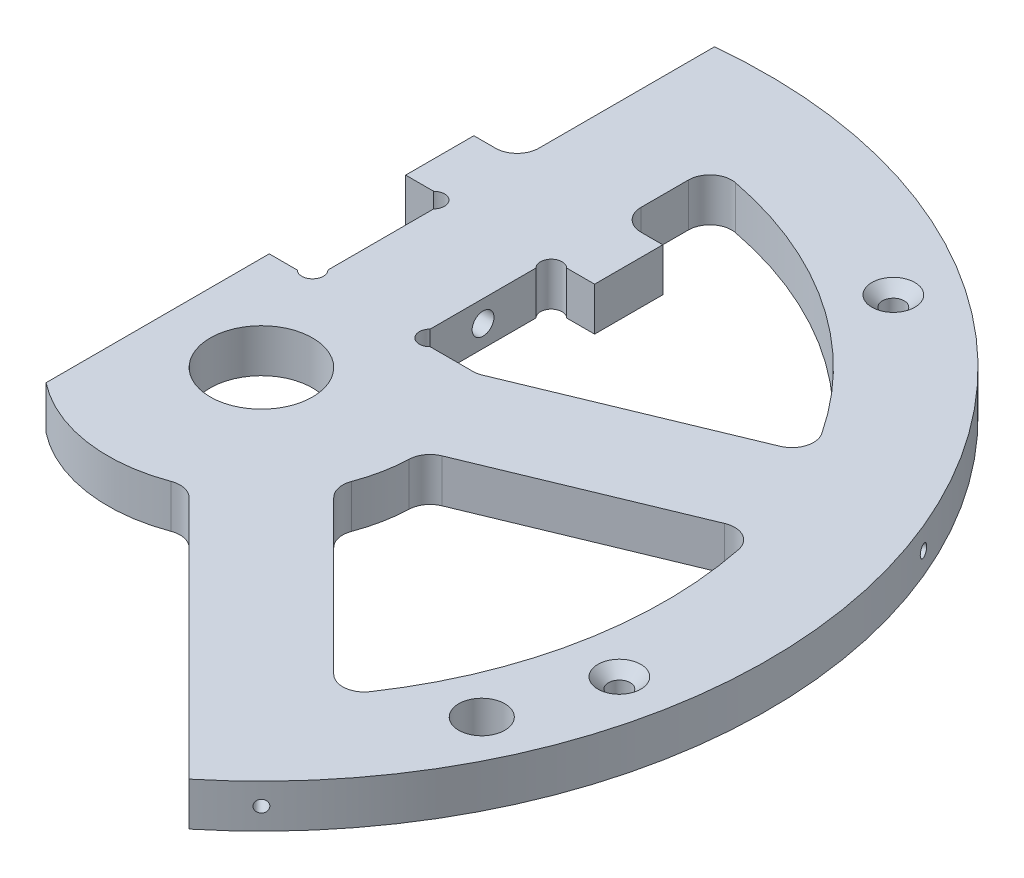
SolidWorks part; units mm, degrees
material "6061 Alloy"
ref_plane "Front Plane" through (0, 0, 0) normal (0, 0, 1) x (1, 0, 0)
ref_plane "Top Plane" through (0, 0, 0) normal (0, 1, 0) x (1, 0, 0)
ref_plane "Right Plane" through (0, 0, 0) normal (1, 0, 0) x (0, 0, -1)
sketch "Sketch1" plane through (0, 0, 0) normal (0, 1, 0) x (1, 0, 0)
  line L0 (0, 0) -> (0, 74.3) construction
  line L1 (0, 0) -> (52.538, -52.538) construction
  line L2 (20.3033, -9.6967) -> (46.898, -36.2914)
  line L3 (7.5, 15) -> (7.5, 35)
  line L4 (-7.5, -3.1066) -> (-5.3033, -5.3033) construction
  line L5 (-7.5, 21.2132) -> (-7.5, 14.1697) construction
  line L6 (-7.5, -3.1066) -> (-7.5, 74.3) construction
  line L7 (7.5, 3.1066) -> (7.5, 74.3) construction
  line L8 (-7.5, -3.1066) -> (47.2347, -57.8413) construction
  line L9 (7.5, 3.1066) -> (57.8413, -47.2347) construction
  line L10 (46.898, -36.2914) -> (57.573, -46.9664) construction
  line L11 (7.5, 58.8238) -> (7.5, 73.9205) construction
  line L12 (0, 0) -> (68.6442, 28.4334) construction
  line L13 (22.4686, 1.1888) -> (57.2162, 15.5818)
  line L14 (-2.8701, 6.9291) -> (0, 8.1179) construction
  line L15 (2.8701, -6.9291) -> (5.7403, -5.7403) construction
  line L16 (2.8701, -6.9291) -> (71.5144, 21.5043) construction
  line L17 (5.7403, -5.7403) -> (13.2403, -2.6336) construction
  line L18 (7.5, 3.1066) -> (13.2403, -2.6336) construction
  line L19 (7.5, 3.1066) -> (7.5, 11.2245) construction
  line L20 (0, 8.1179) -> (7.5, 11.2245) construction
  line L21 (7.5, 11.2245) -> (9.0849, 11.881) construction
  line L22 (-2.8701, 6.9291) -> (65.7741, 35.3625) construction
  line L23 (51.476, 29.44) -> (65.4235, 35.2172) construction
  line L24 (65.4235, 35.2172) -> (65.7741, 35.3625)
  line L25 (57.2162, 15.5818) -> (71.1638, 21.3591) construction
  line L26 (71.1638, 21.3591) -> (71.5144, 21.5043)
  line L27 (13.2403, -2.6336) -> (20.3033, -9.6967) construction
  line L28 (13.85, 5) -> (7.5, 5) construction
  line L29 (13.85, 17.7321) -> (13.85, 15) construction
  line L30 (13.85, 45) -> (7.5, 45)
  line L31 (-13.85, 17.7321) -> (-13.85, 15) construction
  line L32 (13.85, 5) -> (-13.85, 45) construction
  line L33 (13.85, 45) -> (-13.85, 5) construction
  line L34 (-13.85, 35) -> (-7.5, 35)
  line L35 (-13.85, 35) -> (-13.85, 15) construction
  line L36 (-16.7705, 15) -> (-7.5, 15)
  line L37 (-7.5, 35) -> (-7.5, 15)
  line L38 (7.5, 15) -> (16.6148, 15)
  line L39 (7.5, 15) -> (7.5, 35)
  line L40 (7.5, 35) -> (13.85, 35)
  line L41 (13.85, 15) -> (13.85, 35) construction
  line L42 (13.2403, -2.6336) -> (22.4686, 1.1888) construction
  line L43 (7.5, 5) -> (-7.5274, 5) construction
  line L44 (-7.5, 5) -> (-13.85, 5) construction
  line L45 (-7.5274, 5) -> (0, 5) construction
  line L46 (0, 5) -> (-7.5, 5) construction
  line L47 (13.85, 5) -> (13.85, 13.8548) construction
  line L48 (16.6148, 15) -> (16.7283, 15.047)
  line L49 (16.7283, 15.047) -> (51.476, 29.44)
  line L50 (13.85, 13.8548) -> (13.85, 17.7321) construction
  line L51 (9.0849, 11.881) -> (13.85, 13.8548) construction
  line L52 (7.5, 11.2245) -> (7.5, 21.2132) construction
  line L53 (7.5, 21.2132) -> (7.5, 14.1697) construction
  line L54 (-5.3033, -5.3033) -> (9.6967, -20.3033) construction
  line L55 (9.6967, -20.3033) -> (46.9664, -57.573)
  line L56 (-7.5, -3.1066) -> (-7.5, 0) construction
  line L57 (-7.5, 0) -> (-7.5, 5) construction
  line L58 (-13.85, 5) -> (-13.85, 17.7321) construction
  line L59 (-7.5, 5) -> (-7.5, 21.2132) construction
  line L60 (-7.5, 14.1697) -> (-7.5, 15) construction
  line L61 (-7.5, 15) -> (-7.5, 35) construction
  line L62 (-13.85, 15) -> (-13.85, 35) construction
  line L63 (-13.85, 35) -> (-13.85, 45)
  line L64 (13.85, 15) -> (13.85, 35) construction
  line L65 (13.85, 35) -> (13.85, 45)
  line L66 (0, 45) -> (-7.5, 45) construction
  line L67 (-7.5, 45) -> (-13.85, 45)
  line L68 (7.5, 45) -> (0, 45) construction
  line L69 (7.5, 14.1697) -> (7.5, 15) construction
  line L70 (7.5, 35.8303) -> (7.5, 45) construction
  line L71 (7.5, 45) -> (7.5, 58.8238)
  line L72 (7.5, 35) -> (7.5, 35.8303) construction
  line L73 (-7.5, 35) -> (-7.5, 35.8303) construction
  line L74 (-7.5, 45) -> (-7.5, 73.9205)
  line L75 (-7.5, 35.8303) -> (-7.5, 45) construction
  line L77 (13.85, 13.8548) -> (16.6148, 15) construction
  arc A0 (46.9664, -57.573) -> (-7.5, 73.9205) centre (0, 0) ccw
  arc A1 (46.898, -36.2914) -> (57.2162, 15.5818) centre (0, 0) ccw
  arc A2 (-7.5, 73.9205) -> (46.9664, -57.573) centre (0, 0) ccw construction
  circle A3 centre (0, 0) radius 74.3 construction
  arc A4 (41.9314, -41.9314) -> (46.898, -36.2914) centre (0, 0) ccw construction
  circle A5 centre (0, 0) radius 59.3 construction
  arc A6 (36.2914, -46.898) -> (41.9314, -41.9314) centre (0, 0) ccw construction
  arc A7 (-7.5, 58.8238) -> (36.2914, -46.898) centre (0, 0) ccw construction
  arc A8 (7.5, 58.8238) -> (0, 59.3) centre (0, 0) ccw construction
  arc A9 (0, 59.3) -> (-7.5, 58.8238) centre (0, 0) ccw construction
  arc A10 (57.2162, 15.5818) -> (54.7861, 22.6931) centre (0, 0) ccw construction
  arc A11 (51.476, 29.44) -> (7.5, 58.8238) centre (0, 0) ccw
  arc A12 (54.7861, 22.6931) -> (51.476, 29.44) centre (0, 0) ccw construction
  arc A13 (20.3033, -9.6967) -> (22.4686, 1.1888) centre (0, 0) ccw
  circle A14 centre (0, 0) radius 7.5
  arc A15 (9.6967, -20.3033) -> (15.9099, -15.9099) centre (0, 0) ccw construction
  arc A16 (15.9099, -15.9099) -> (20.3033, -9.6967) centre (0, 0) ccw construction
  arc A17 (22.4686, 1.1888) -> (20.7873, 8.6104) centre (0, 0) ccw construction
  arc A18 (16.7283, 15.047) -> (13.85, 17.7321) centre (0, 0) ccw construction
  arc A19 (20.7873, 8.6104) -> (16.7283, 15.047) centre (0, 0) ccw construction
  arc A20 (13.85, 17.7321) -> (1.7801, 22.4295) centre (0, 0) ccw construction
  arc A21 (-7.5, 21.2132) -> (-13.85, 17.7321) centre (0, 0) ccw construction
  arc A22 (1.7801, 22.4295) -> (-13.85, 17.7321) centre (0, 0) ccw construction
  arc A23 (7.5, 21.2132) -> (0, 22.5) centre (0, 0) ccw construction
  arc A24 (0, 22.5) -> (-7.5, 21.2132) centre (0, 0) ccw construction
  arc A25 (-1.7801, 22.4295) -> (-13.85, 17.7321) centre (0, 0) ccw construction
  arc A26 (-16.7705, 15) -> (9.6967, -20.3033) centre (0, 0) ccw
  arc A27 (-13.85, 17.7321) -> (-16.7705, 15) centre (0, 0) ccw construction
  arc A28 (-16.7705, 15) -> (-1.7801, 22.4295) centre (0, 0) ccw construction
  arc A29 (-13.85, 17.7321) -> (-16.7705, 15) centre (0, 0) ccw construction
  arc A30 (-13.85, 17.7321) -> (-16.7705, 15) centre (0, 0) ccw construction
  arc A31 (-16.7705, 15) -> (7.5, 21.2132) centre (0, 0) ccw construction
  point P77 (0, 25)
  dimension "D1" = 148.6
  dimension "D11" = 45
  dimension "D12" = 15
  dimension "D2" = 135
  dimension "D6" = 67.5
  dimension "D9" = 27.7
  dimension "D10" = 40
  dimension "D13" = 5
  dimension "D14" = 10
  dimension "D15" = 10
  dimension "D3" = 7.5
  dimension "D4" = 7.5
  dimension "D5" = 15
  dimension "D7" = 7.5
  dimension "D8" = 7.5
extrude "Boss-Extrude1" add sketch "Sketch1" along normal mid plane 6.35 contours L31 A26 L55 A0 L74 L67 L63 L34 L37 L36 L49 A18 L29 L38 L3 L40 L65 L30 L71 A11 L2 A13 L13 A1 A14
hole_wizard "M5x0.8 Tapped Hole2" positions "Sketch2" profile "Sketch3" tap size "M5x0.8" standard "ANSI Metric"
sketch "Sketch2" plane through (0, 3.175, 0) normal (0, 1, 0) x (1, 0, 0)
  line L1 (0, 0) -> (-13.4234, 7.75) construction
  line L3 (13.4234, 7.75) -> (0, 0) construction
  line L4 (0, 0) -> (0, -15.5) construction
  circle A0 centre (0, 0) radius 15.5 construction
  point P10 (-13.4234, 7.75)
  point P12 (13.4234, 7.75)
  point P16 (0, -15.5)
  dimension "D1" = 31
  dimension "D2" = 120
  dimension "D3" = 120
sketch "Sketch3" plane through (0, 3.175, 15.5) normal (1, 0, 0) x (0, 0, 1)
  line L0 (0, 0) -> (0, 6.35)
  line L1 (0, 6.35) -> (2.1, 6.35)
  line L2 (2.1, 6.35) -> (2.1, 0)
  line L5 (2.1, 0) -> (0, 0)
  line L11 (0, -6.35) -> (0, 107.95) construction
  dimension "Thru Tap Drill Dia." = 4.2
  dimension "Thru Tap Drill Depth" = 6.35
ref_plane "Plane1" through (0, 0, -74.3) normal (0, 0, -1) x (-1, 0, 0)
hole_wizard "M2.2x0.45 Tapped Hole1" positions "Sketch4" profile "Sketch5" tap size "M2.2x0.45" standard "ANSI Metric"
sketch "Sketch4" plane through (0, 0, -74.3) normal (0, 0, -1) x (-1, 0, 0)
  point P0 (0, 0)
sketch "Sketch5" plane through (0, 0, -74.3) normal (1, 0, 0) x (0, 1, 0)
  line L0 (0, 0) -> (0, 10.5258)
  line L1 (0, 10.5258) -> (0.875, 10)
  line L2 (0.875, 10) -> (0.875, 0)
  line L5 (0.875, 0) -> (0, 0)
  line L10 (0, 10.5258) -> (-0.875, 10) construction
  line L11 (0, -6.35) -> (0, 107.95) construction
  dimension "Tap Drill Dia." = 1.75
  dimension "Tap Drill Depth" = 10
  dimension "Drill Angle" = 118
pattern_circular "CirPattern1" count 3 over 135 about axis through (0, 3.175, 0) along (0, -1, 0) of "M2.2x0.45 Tapped Hole1"
hole_wizard "M3 Clearance Hole1" positions "Sketch6" profile "Sketch7" hole size "M3" standard "ANSI Metric"
sketch "Sketch6" plane through (-7.5, 0, 0) normal (-1, 0, 0) x (0, 0, 1)
  line L1 (-35, 3.175) -> (-15, 3.175)
  line L2 (-35, 3.175) -> (-35, -3.175)
  line L3 (-35, -3.175) -> (-15, -3.175)
  line L4 (-15, 3.175) -> (-15, -3.175)
  line L5 (-35, 3.175) -> (-15, -3.175) construction
  line L6 (-35, -3.175) -> (-15, 3.175) construction
  point P97 (-25, 0)
sketch "Sketch7" plane through (-7.5, 0, -25) normal (0, 1, 0) x (0, 0, 1)
  line L0 (0, 0) -> (0, 15)
  line L1 (0, 15) -> (1.6, 15)
  line L2 (1.6, 15) -> (1.6, 0)
  line L5 (1.6, 0) -> (0, 0)
  line L11 (0, -6.35) -> (0, 107.95) construction
  dimension "Thru Hole Dia." = 3.2
  dimension "Thru Hole Depth" = 15
hole_wizard "CSK for M3 Flat Head Machine Screw1" positions "Sketch8" profile "Sketch9" countersink size "M3" standard "ANSI Metric" end condition up to next
sketch "Sketch8" plane through (0, 3.175, 0) normal (0, 1, 0) x (1, 0, 0)
  line L0 (32.9453, 49.3061) -> (41.2789, 61.7782) construction
  line L2 (58.1606, -11.5689) -> (72.8723, -14.4952) construction
  arc A0 (51.476, 29.44) -> (7.5, 58.8238) centre (0, 0) ccw construction
  arc A1 (46.9664, -57.573) -> (-7.5, 73.9205) centre (0, 0) ccw construction
  arc A2 (46.898, -36.2914) -> (57.2162, 15.5818) centre (0, 0) ccw construction
  point P19 (37.1121, 55.5422)
  point P21 (65.5165, -13.032)
sketch "Sketch9" plane through (65.5165, 3.175, 13.032) normal (1, 0, 0) x (0, 0, 1)
  line L0 (0, 0) -> (0, 6.35)
  line L1 (0, 6.35) -> (1.6, 6.35)
  line L2 (1.6, 6.35) -> (1.6, 1.55)
  line L3 (1.6, 1.55) -> (3.15, 0)
  line L5 (3.15, 0) -> (0, 0)
  line L6 (-1.6, 1.55) -> (-3.15, 0) construction
  line L11 (0, -6.35) -> (0, 107.95) construction
  dimension "Thru Hole Dia." = 3.2
  dimension "Thru Hole Depth" = 6.35
  dimension "Near C'Sink Dia." = 6.3
  dimension "Near C'Sink Angle" = 90
sketch "Sketch10" plane through (0, 3.175, 0) normal (0, 1, 0) x (1, 0, 0)
  line L1 (-7.5, 35) -> (-8.6225, 35)
  line L2 (-7.5, 35) -> (-7.5, 33.8775)
  line L3 (-7.5, 33.8775) -> (-8.6225, 33.8775)
  line L4 (-8.6225, 35) -> (-8.6225, 33.8775)
  line L5 (-7.5, 35) -> (-8.6225, 33.8775) construction
  line L6 (-7.5, 33.8775) -> (-8.6225, 35) construction
  line L7 (-7.5, 15) -> (-8.6225, 15)
  line L8 (-7.5, 15) -> (-7.5, 16.1225)
  line L9 (-7.5, 16.1225) -> (-8.6225, 16.1225)
  line L10 (-8.6225, 15) -> (-8.6225, 16.1225)
  line L11 (-7.5, 15) -> (-8.6225, 16.1225) construction
  line L12 (-7.5, 16.1225) -> (-8.6225, 15) construction
  line L13 (7.5, 15) -> (8.6225, 15)
  line L14 (7.5, 15) -> (7.5, 16.1225)
  line L15 (7.5, 16.1225) -> (8.6225, 16.1225)
  line L16 (8.6225, 15) -> (8.6225, 16.1225)
  line L17 (7.5, 15) -> (8.6225, 16.1225) construction
  line L18 (7.5, 16.1225) -> (8.6225, 15) construction
  line L19 (7.5, 35) -> (8.6225, 35)
  line L20 (7.5, 35) -> (7.5, 33.8775)
  line L21 (7.5, 33.8775) -> (8.6225, 33.8775)
  line L22 (8.6225, 35) -> (8.6225, 33.8775)
  line L23 (7.5, 35) -> (8.6225, 33.8775) construction
  line L24 (7.5, 33.8775) -> (8.6225, 35) construction
  circle A0 centre (-8.6225, 16.1225) radius 1.5875
  circle A1 centre (8.6225, 16.1225) radius 1.5875
  circle A2 centre (8.6225, 33.8775) radius 1.5875
  circle A3 centre (-8.6225, 33.8775) radius 1.5875
  point P4 (-8.0613, 34.4387)
  point P10 (-8.0613, 15.5613)
  point P16 (8.0613, 15.5613)
  point P22 (8.0613, 34.4387)
  line M24 (16.6148, 15) -> (7.5, 15)
  line M25 (7.5, 15) -> (7.5, 35)
  line M26 (7.5, 35) -> (13.85, 35)
  line M31 (-7.5, 15) -> (-16.7705, 15)
  line M38 (-13.85, 35) -> (-7.5, 35)
  line M39 (-7.5, 35) -> (-7.5, 15)
  dimension "D1" = 3.175
extrude "Cut-Extrude1" cut sketch "Sketch10" against normal up to next contours A0 M31 | A0 M39 | A1 M24 | A1 M25 | A2 M25 | A2 M26 | A3 M39 | A3 M38
fillet "Fillet1" radius 3.175 10 edges at (9.6967, 0, 20.3033) (-7.5, 0, -45) (51.476, 0, -29.44) (7.5, 0, -58.8238) (7.5, 0, -45) (16.6148, 0, -15) (46.898, 0, 36.2914) (57.2162, 0, -15.5818) (20.3033, 0, 9.6967) (22.4686, 0, -1.1888)
sketch "Sketch11" plane through (0, 3.175, 0) normal (0, 1, 0) x (1, 0, 0)
  line L0 (-13.85, 15) -> (-13.85, -17.7321)
  line L1 (-13.85, 15) -> (-23.5, 15)
  line L2 (-13.85, -17.7321) -> (-23.5, -17.7321)
  line L3 (-23.5, 15) -> (-23.5, -17.7321)
  line L4 (-13.85, 35) -> (-13.85, 45) construction
  line L5 (-16.7705, 15) -> (-9.7451, 15) construction
  arc A0 (-16.7705, 15) -> (7.8546, -21.0845) centre (0, 0) ccw construction
  dimension "D1" = 1
extrude "Cut-Extrude2" cut sketch "Sketch11" against normal up to next
hole_wizard "1/4 Clearance Hole1" positions "Sketch12" profile "Sketch13" hole size "1/4" standard "ANSI Inch" end condition up to next
sketch "Sketch12" plane through (0, 3.175, 0) normal (0, 1, 0) x (1, 0, 0)
  line L0 (53.7441, -25.0613) -> (67.3387, -31.4005) construction
  line L2 (11.2081, -21.8147) -> (46.9664, -57.573) construction
  arc A0 (46.9664, -57.573) -> (-7.5, 73.9205) centre (0, 0) ccw construction
  arc A1 (49.1414, -33.1906) -> (58.1022, 11.8585) centre (0, 0) ccw construction
  point P43 (60.5414, -28.2309)
  point P46 (50.1847, -31.5908)
  point P51 (60.2897, -28.7645)
  dimension "D1" = 20
sketch "Sketch13" plane through (60.5414, 3.175, 28.2309) normal (1, 0, 0) x (0, 0, 1)
  line L0 (0, 0) -> (0, 6.35)
  line L1 (0, 6.35) -> (3.3782, 6.35)
  line L2 (3.3782, 6.35) -> (3.3782, 0)
  line L5 (3.3782, 0) -> (0, 0)
  line L11 (0, -6.35) -> (0, 107.95) construction
  dimension "Thru Hole Dia." = 6.7564
  dimension "Thru Hole Depth" = 6.35
